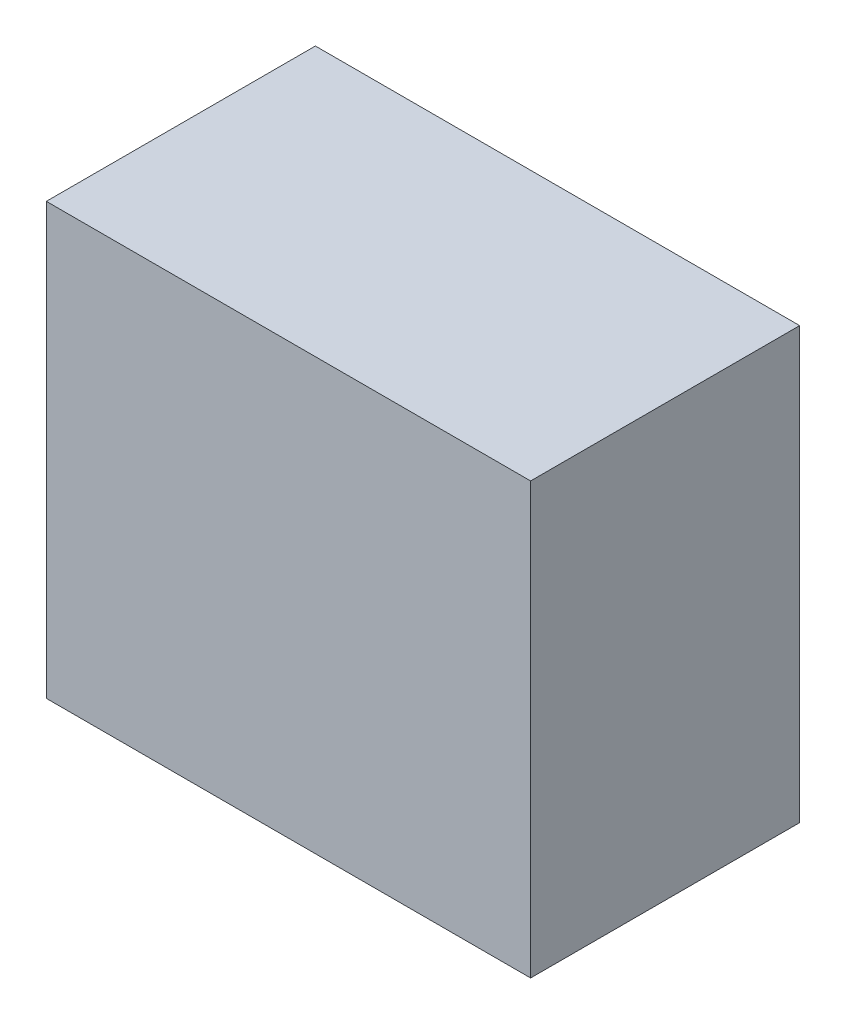
SolidWorks part; units mm, degrees
ref_plane "Front Plane" through (0, 0, 0) normal (0, 0, 1) x (1, 0, 0)
ref_plane "Top Plane" through (0, 0, 0) normal (0, 1, 0) x (1, 0, 0)
ref_plane "Right Plane" through (0, 0, 0) normal (1, 0, 0) x (0, 0, -1)
other "Configuration Table"
sketch "Sketch1" plane through (0, 0, 0) normal (0, 0, 1) x (1, 0, 0)
  line L1 (730, 1584) -> (748, 1584)
  line L2 (730, 1584) -> (730, 1600)
  line L3 (730, 1600) -> (748, 1600)
  line L4 (748, 1584) -> (748, 1600)
extrude "DET2_reed_sensor_braketi_1" add sketch "Sketch1" against normal blind 10 from offset 2 separate body
